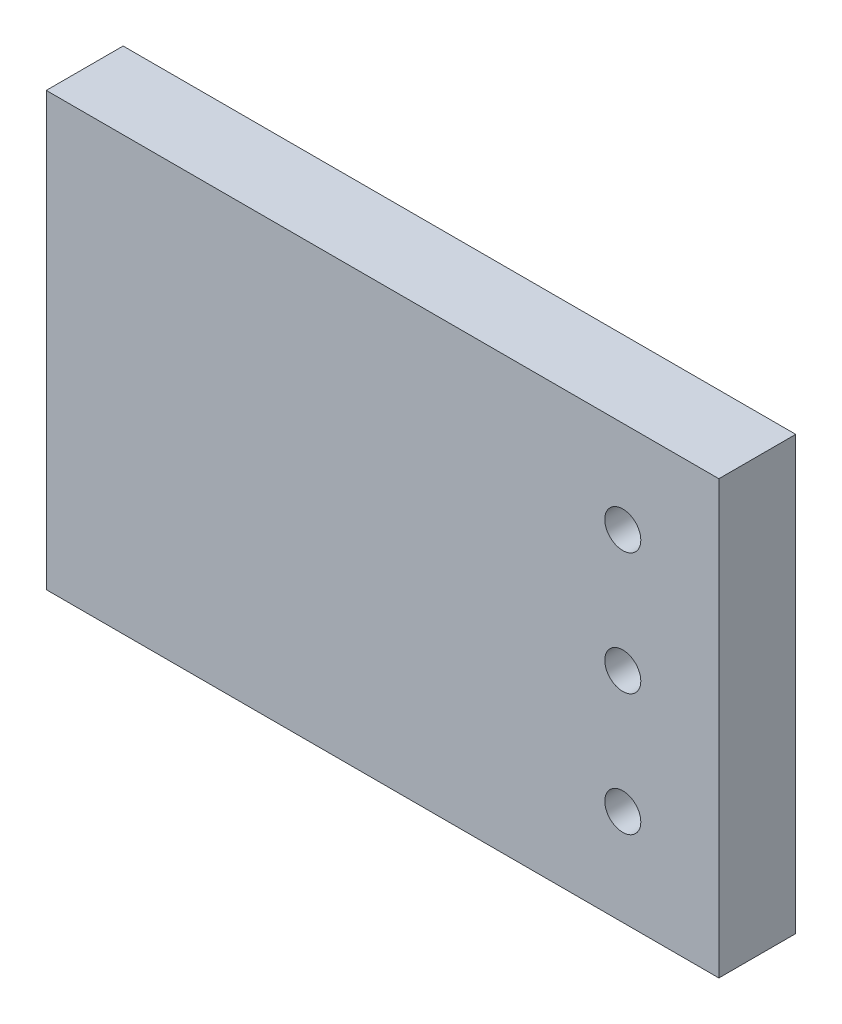
SolidWorks part; units mm, degrees
ref_plane "Front Plane" through (0, 0, 0) normal (0, 0, 1) x (1, 0, 0)
ref_plane "Top Plane" through (0, 0, 0) normal (0, 1, 0) x (1, 0, 0)
ref_plane "Right Plane" through (0, 0, 0) normal (1, 0, 0) x (0, 0, -1)
sketch "Sketch1" plane through (0, 0, 0) normal (0, 0, 1) x (1, 0, 0)
  line L1 (0, 0) -> (14, 0)
  line L2 (0, 0) -> (0, -9)
  line L3 (0, -9) -> (14, -9)
  line L4 (14, 0) -> (14, -9)
  dimension "D1" = 14
  dimension "D2" = 9
extrude "Boss-Extrude1" add sketch "Sketch1" along normal blind 1.6
sketch "Sketch2" plane through (0, 0, 1.6) normal (0, 0, 1) x (1, 0, 0)
  line L0 (14, -9) -> (14, 0) construction
  line L1 (0, -9) -> (14, -9) construction
  circle A0 centre (12, -7) radius 0.375
  circle A1 centre (12, -4.46) radius 0.375
  circle A2 centre (12, -1.92) radius 0.375
  dimension "D2" = 2
  dimension "D3" = 0.75
  dimension "D1" = 2
  dimension "D4" = 2.54
  dimension "D5" = 2.54
extrude "Cut-Extrude1" cut sketch "Sketch2" against normal through all
sketch "Sketch3" plane through (0, 0, 1.6) normal (0, 0, 1) x (1, 0, 0)
  point P0 (7, -4.5)
